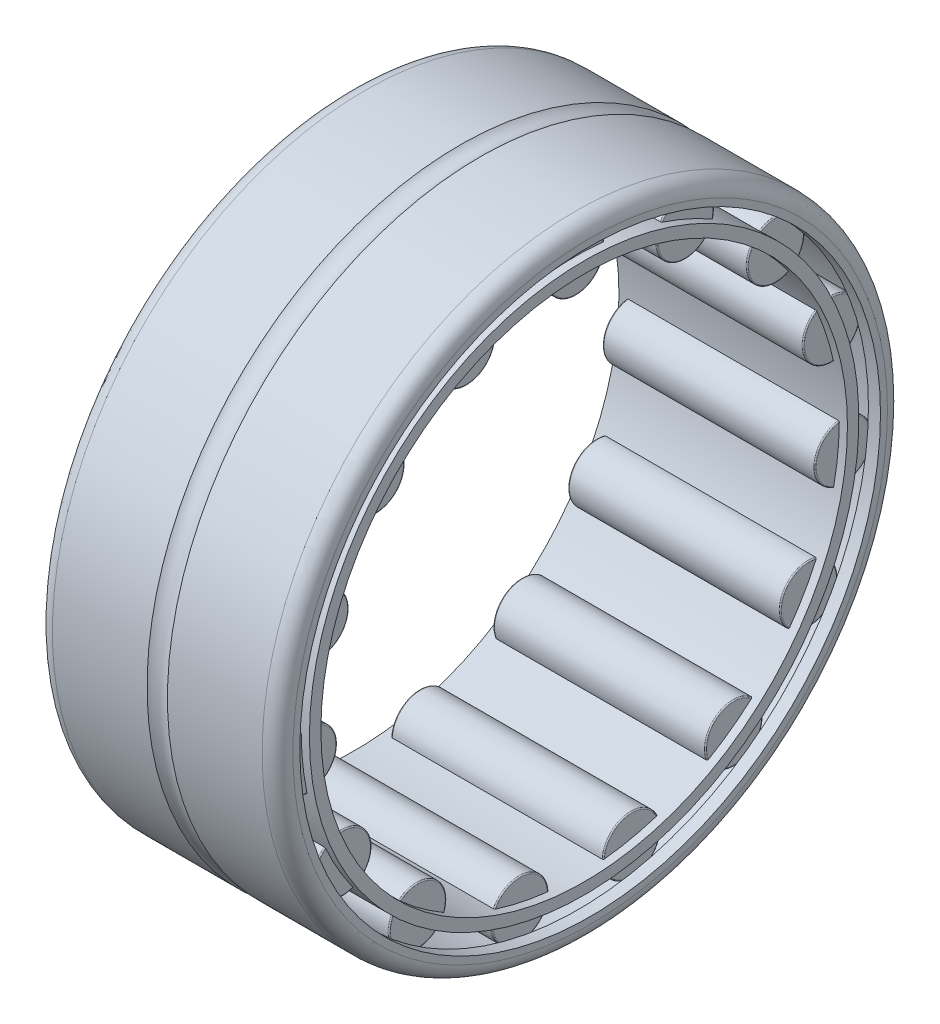
SolidWorks part; units mm, degrees
ref_plane "Plane1" through (0, 0, 0) normal (0, 0, 1) x (1, 0, 0)
ref_plane "Plane2" through (0, 0, 0) normal (0, 1, 0) x (1, 0, 0)
ref_plane "Plane3" through (0, 0, 0) normal (1, 0, 0) x (0, 0, -1)
sketch "Clipboard" plane through (0, 0, 0) normal (0, 0, 1) x (1, 0, 0)
  line L0 (-10, 0) -> (10, 0) construction
  line L1 (41.1529, 1.4371) -> (62.7517, -4.3503)
  line L2 (41.1529, 1.4371) -> (75.4583, 10.6292)
  line L3 (41.1529, 1.4371) -> (62.7517, -4.3503)
  line L4 (41.1529, 1.4371) -> (-22.3471, -0.7804)
  dimension "BallCLRad" = 35.5155
  dimension "Count" = 15
  dimension "Show_count" = 15
  dimension "Max_count" = 15
  dimension "Min_count" = 2
  dimension "Bore" = 63.5
sketch "InnRacSke" plane through (0, 0, 0) normal (0, 0, 1) x (1, 0, 0)
  line L0 (-14.2875, 38.3286) -> (-15.875, 38.3286)
  line L1 (-15.875, 38.3286) -> (-15.875, 39.243)
  line L2 (-13.843, 41.275) -> (-1.344, 41.275)
  line L3 (1.344, 41.275) -> (13.843, 41.275)
  line L4 (15.875, 39.243) -> (15.875, 38.3286)
  line L5 (15.875, 38.3286) -> (14.2875, 38.3286)
  line L6 (14.2875, 38.3286) -> (14.2875, 39.2811)
  line L7 (14.2875, 39.2811) -> (-14.2875, 39.2811)
  line L8 (-14.2875, 39.2811) -> (-14.2875, 38.3286)
  line L9 (-31.75, 0) -> (31.75, 0) construction
  arc A0 (-15.875, 39.243) -> (-13.843, 41.275) centre (-13.843, 39.243) cw
  arc A1 (-1.344, 41.275) -> (1.344, 41.275) centre (0, 42.799) ccw
  arc A2 (13.843, 41.275) -> (15.875, 39.243) centre (13.843, 39.243) cw
  dimension "radius" = 2.032
  dimension "D1" = 78.5622
  dimension "OD" = 82.55
  dimension "Width" = 31.75
  dimension "groove_dp" = 0.9525
  dimension "Cyl_Len" = 28.575
  dimension "offset" = 1.524
  dimension "halfCyl" = 14.2875
revolve "Race" add sketch "InnRacSke" angle 360 about L9
sketch "RolDetSke" plane through (0, 0, 0) normal (0, 0, 1) x (1, 0, 0)
  line L0 (-14.0018, 39.1427) -> (-14.0017, 35.5155)
  line L1 (-14.0017, 35.5155) -> (14.0017, 35.5155)
  line L2 (14.0017, 35.5155) -> (14.0018, 39.1427)
  line L3 (13.8506, 39.2938) -> (-13.8506, 39.2938)
  line L4 (-28.575, 35.5155) -> (28.575, 35.5155) construction
  arc A0 (14.0018, 39.1427) -> (13.8506, 39.2938) centre (13.8506, 39.1427) ccw
  arc A1 (-13.8506, 39.2938) -> (-14.0018, 39.1427) centre (-13.8506, 39.1427) ccw
  dimension "Roller_radius" = 0.1511
  dimension "Roller_diameter" = 7.5565
  dimension "Roller_length" = 28.0035
  dimension "RollerCLRad" = 35.5155
  dimension "halfLength" = 14.0017
revolve "RollerDetailed" add sketch "RolDetSke" angle 360 about L4
ref_axis "Axis1" through (-50, 0, 0) along (1, 0, 0)
sketch "CagSpiSke" plane through (0, 0, 0) normal (0, 0, 1) x (1, 0, 0)
  line L0 (15.0812, 34.7599) -> (15.0812, 36.2712)
  line L1 (15.0812, 36.2712) -> (-15.0813, 36.2712)
  line L2 (-15.0813, 36.2712) -> (-15.0813, 34.7599)
  line L3 (-15.0813, 34.7599) -> (15.0812, 34.7599)
  line L4 (-31.75, 0) -> (31.75, 0) construction
  dimension "Cage_width" = 30.1625
  dimension "D2" = 69.5198
  dimension "Cage_thickness" = 1.5113
  dimension "halfWidth" = 15.0812
revolve "CageSpine" add sketch "CagSpiSke" angle 360 about L4
pattern_circular "RollersDetailed" count 15 every 24 about axis through (-50, 0, 0) along (1, 0, 0) of "RollerDetailed"
sketch "RolSimSke" plane through (0, 0, 0) normal (0, 0, 1) x (1, 0, 0)
  line L0 (-25.4, 0) -> (25.4, 0) construction
  line L2 (-13.8506, 39.3065) -> (13.8506, 39.3065)
  line L3 (-14.0018, 39.1554) -> (-14.0018, 31.9011)
  line L4 (-13.8506, 31.75) -> (13.8506, 31.75)
  line L5 (14.0017, 39.1554) -> (14.0017, 31.9011)
  arc A0 (-14.0018, 31.9011) -> (-13.8506, 31.75) centre (-13.8506, 31.9011) ccw
  arc A1 (-13.8506, 39.3065) -> (-14.0018, 39.1554) centre (-13.8506, 39.1554) ccw
  arc A2 (14.0017, 39.1554) -> (13.8506, 39.3065) centre (13.8506, 39.1554) ccw
  arc A3 (13.8506, 31.75) -> (14.0017, 31.9011) centre (13.8506, 31.9011) ccw
  point P10 (-14.0018, 31.75)
  point P15 (14.0017, 39.3065)
  point P18 (14.0017, 31.75)
  dimension "Bore" = 63.5
  dimension "Roller_diameter" = 7.5565
  dimension "Roller_length" = 28.0035
  dimension "D1" = 0.1511
  dimension "halfWidth" = 14.0017
revolve "RollersSimplified" [suppressed] add sketch "RolSimSke" angle 360 about L0
equation "\"BallCLRad@Clipboard\" =  ( \"D1@InnRacSke\" + \"Bore@Clipboard\" )  / 4"
equation "\"RollerCLRad@RolDetSke\" = \"BallCLRad@Clipboard\""
equation "\"offset@InnRacSke\" = \"radius@InnRacSke\" * .75"
equation "\"halfCyl@InnRacSke\" = \"Cyl_Len@InnRacSke\" / 2"
equation "\"Roller_diameter@RolDetSke\" =  ( \"D1@InnRacSke\" - \"Bore@Clipboard\" )  / 2 + .001"
equation "\"Roller_radius@RolDetSke\" = \"Roller_diameter@RolDetSke\" / 50"
equation "\"Roller_length@RolDetSke\" = \"Cyl_Len@InnRacSke\" * .98"
equation "\"halfLength@RolDetSke\" = \"Roller_length@RolDetSke\" / 2"
equation "\"Cage_width@CagSpiSke\" =  ( \"Cyl_Len@InnRacSke\" + \"Width@InnRacSke\" )  / 2"
equation "\"halfWidth@CagSpiSke\" = \"Cage_width@CagSpiSke\" / 2"
equation "\"Cage_thickness@CagSpiSke\"  = \"Roller_diameter@RolDetSke\" / 5"
equation "\"D2@CagSpiSke\" =  \"RollerCLRad@RolDetSke\" * 2 - \"Cage_thickness@CagSpiSke\""
equation "\"Roller_length@RolSimSke\" = \"Cyl_Len@InnRacSke\" * .98"
equation "\"halfWidth@RolSimSke\" = \"Roller_length@RolSimSke\" / 2"
equation "\"D1@RolSimSke\" = \"Roller_radius@RolDetSke\""
equation "\"Roller_diameter@RolSimSke\" =  ( \"D1@InnRacSke\" - \"Bore@Clipboard\" )  / 2 + .001"
equation "\"Max_count@Clipboard\" = int( 3.14159265 / atn(( \"Roller_diameter@RolDetSke\" / 2) / sqr( \"RollerCLRad@RolDetSke\"  *  \"RollerCLRad@RolDetSke\" - ( \"Roller_diameter@RolDetSke\" / 2) *  ( \"Roller_diameter@RolDetSke\" / 2))))"
equation "\"Max_count@Clipboard\" = ((sgn( \"Max_count@Clipboard\" - \"Count@Clipboard\" )-1)*( \"Max_count@Clipboard\" - \"Count@Clipboard\" ))/-2+ \"Count@Clipboard\""
equation "\"Count@RollersDetailed\" = int( \"Show_count@Clipboard\" ) "
equation "\"Count@RollersDetailed\" = ((sgn( \"Count@RollersDetailed\" - \"Max_count@Clipboard\" )-1)*( \"Count@RollersDetailed\" - \"Max_count@Clipboard\" ))/-2+ \"Max_count@Clipboard\""
equation "\"Count@RollersDetailed\" = ((sgn( \"Count@RollersDetailed\" - \"Min_count@Clipboard\" )+1)*( \"Count@RollersDetailed\" - \"Min_count@Clipboard\"))/2 +\"Min_count@Clipboard\""
equation "\"Angle@RollersDetailed\" = 360.0 / \"Max_count@Clipboard\""
equation "\"Angle@CageSpine\" =  \"Angle@RollersDetailed\" * ( \"Count@RollersDetailed\" -1 + int( \"Count@RollersDetailed\" / \"Max_count@Clipboard\" ) )  + 0.001 -  int( \"Count@RollersDetailed\" / \"Max_count@Clipboard\" ) * 0.001"
equation "\"Angle@CageSpine\" =  \"Angle@CageSpine\" * int( \"Min_count@Clipboard\" / 2) + int(1 / \"Min_count@Clipboard\")  * 0.001"
equation "\"Bore@RolSimSke\" = \"Bore@Clipboard\""
